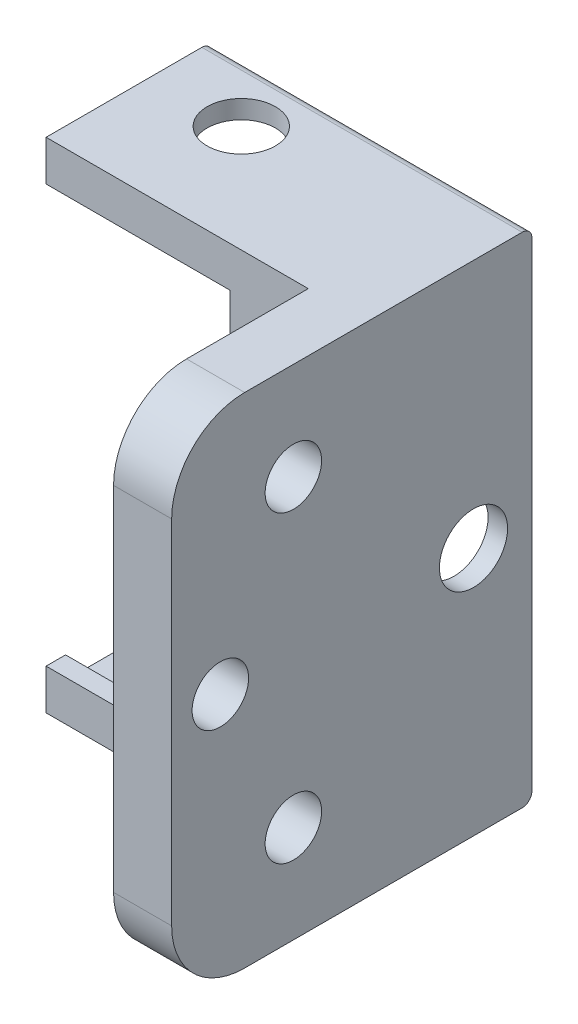
SolidWorks part; units mm, degrees
ref_plane "Front Plane" through (0, 0, 0) normal (0, 0, 1) x (1, 0, 0)
ref_plane "Top Plane" through (0, 0, 0) normal (0, 1, 0) x (1, 0, 0)
ref_plane "Right Plane" through (0, 0, 0) normal (1, 0, 0) x (0, 0, -1)
sketch "Sketch2" plane through (0, 0, 0) normal (0, 0, 1) x (1, 0, 0)
  line L1 (21.85, -23.6) -> (-21.85, -23.6)
  line L2 (21.85, -23.6) -> (21.85, 23.6)
  line L3 (21.85, 23.6) -> (-21.85, 23.6)
  line L4 (-21.85, -23.6) -> (-21.85, 23.6)
  line L5 (21.85, -23.6) -> (-21.85, 23.6) construction
  line L6 (21.85, 23.6) -> (-21.85, -23.6) construction
  line L7 (19.85, -21.4398) -> (-19.85, -21.4398)
  line L8 (19.85, -21.4398) -> (19.85, 21.4398)
  line L9 (19.85, 21.4398) -> (-19.85, 21.4398)
  line L10 (-19.85, -21.4398) -> (-19.85, 21.4398)
  line L11 (19.85, -21.4398) -> (-19.85, 21.4398) construction
  line L12 (19.85, 21.4398) -> (-19.85, -21.4398) construction
  line L13 (19.85, 21.4398) -> (9.85, 21.4398)
  line L14 (19.85, 21.4398) -> (19.85, -21.4398)
  line L15 (19.85, -21.4398) -> (9.85, -21.4398)
  line L16 (9.85, 21.4398) -> (9.85, -21.4398)
  point P0 (0, 0)
  point P6 (0, 0)
  dimension "D1" = 43.7
  dimension "D2" = 47.2
  dimension "D3" = 2
  dimension "D4" = 10
extrude "Boss-Extrude1" add sketch "Sketch2" along normal blind 2 contours L9 L16 L7 L8 | L4 L1 L2 L3 L7 L10 L9 L8
sketch "Sketch3" plane through (0, 0, 2) normal (0, 0, 1) x (1, 0, 0)
  line L8 (-23.85, 25.6) -> (-23.85, -25.6)
  line L9 (-23.85, -25.6) -> (23.85, -25.6)
  line L10 (23.85, -25.6) -> (23.85, 25.6)
  line L11 (23.85, 25.6) -> (-23.85, 25.6)
  line L12 (-23.85, 25.6) -> (-23.85, -25.6)
  line L13 (-23.85, -25.6) -> (23.85, -25.6)
  line L14 (23.85, -25.6) -> (23.85, 25.6)
  line L15 (23.85, 25.6) -> (-23.85, 25.6)
  line L20 (-21.85, 23.6) -> (-21.85, -23.6)
  line L21 (21.85, 23.6) -> (-21.85, 23.6)
  line L22 (21.85, -23.6) -> (21.85, 23.6)
  line L23 (-21.85, -23.6) -> (21.85, -23.6)
  line L24 (-21.85, 23.6) -> (-21.85, -23.6)
  line L25 (21.85, 23.6) -> (-21.85, 23.6)
  line L26 (21.85, -23.6) -> (21.85, 23.6)
  line L27 (-21.85, -23.6) -> (21.85, -23.6)
  dimension "D1" = 2
  dimension "D2" = 0
extrude "Boss-Extrude2" add sketch "Sketch3" against normal blind 17 contours L12 L13 L14 L15
sketch "Sketch5" plane through (0, -25.6, 0) normal (0, -1, 0) x (1, 0, 0)
  line L0 (-23.85, -15) -> (23.85, -15) construction
  point P0 (0, -9)
  dimension "D1" = 6
sketch "Sketch16" plane through (23.85, 0, 0) normal (1, 0, 0) x (0, 0, -1)
  line L0 (15, -25.6) -> (15, 25.6) construction
  point P0 (9, 0)
  dimension "D1" = 6
hole_wizard "M6 Clearance Hole1" positions "Sketch6" profile "Sketch7" hole size "M6" standard "ANSI Metric" end condition through all
sketch "Sketch6" plane through (0, -25.6, 0) normal (0, -1, 0) x (-1, 0, 0)
  point P0 (0, 9)
sketch "Sketch7" plane through (0, -25.6, -9) normal (1, 0, 0) x (0, 0, -1)
  line L0 (0, 0) -> (0, 51.2)
  line L1 (0, 51.2) -> (3.5, 51.2)
  line L2 (3.5, 51.2) -> (3.5, 0)
  line L5 (3.5, 0) -> (0, 0)
  line L11 (0, -6.35) -> (0, 107.95) construction
  dimension "Thru Hole Dia." = 7
  dimension "Thru Hole Depth" = 51.2
hole_wizard "M6 Clearance Hole2" positions "Sketch17" profile "Sketch18" hole size "M6" standard "ANSI Metric" end condition through all
sketch "Sketch17" plane through (23.85, 0, 0) normal (1, 0, 0) x (0, 0, -1)
  point P0 (9, 0)
sketch "Sketch18" plane through (23.85, 0, -9) normal (0, 1, 0) x (0, 0, -1)
  line L0 (0, 0) -> (0, 47.7)
  line L1 (0, 47.7) -> (3.5, 47.7)
  line L2 (3.5, 47.7) -> (3.5, 0)
  line L5 (3.5, 0) -> (0, 0)
  line L11 (0, -6.35) -> (0, 107.95) construction
  dimension "Thru Hole Dia." = 7
  dimension "Thru Hole Depth" = 47.7
sketch "Sketch9" plane through (0, 0, 2) normal (0, 0, 1) x (1, 0, 0)
  line L0 (23.85, 25.6) -> (-23.85, 25.6) construction
  line L1 (23.85, -25.6) -> (17.881, -25.6)
  line L2 (23.85, -25.6) -> (23.85, 25.6)
  line L3 (23.85, 25.6) -> (17.881, 25.6)
  line L4 (17.881, -25.6) -> (17.881, 25.6)
extrude "Boss-Extrude3" add sketch "Sketch9" along normal blind 20
sketch "Sketch10" plane through (23.85, 0, 0) normal (1, 0, 0) x (0, 0, -1)
  line L0 (-9.5, 15.6) -> (-9.5, -15.6)
  line L1 (-22, -25.6) -> (-22, 25.6) construction
  line L2 (15, -25.6) -> (-22, -25.6) construction
  line L3 (15, 25.6) -> (-22, 25.6) construction
  point P3 (-9.5, 0)
  point P9 (-17, 0)
  dimension "D1" = 12.5
  dimension "D2" = 10
  dimension "D3" = 10
  dimension "D4" = 5
hole_wizard "M5 Clearance Hole1" positions "Sketch11" profile "Sketch12" hole size "M5" standard "ANSI Metric" end condition through all
sketch "Sketch11" plane through (23.85, 0, 0) normal (1, 0, 0) x (0, 0, -1)
  point P0 (-9.5, -15.6)
  point P3 (-9.5, 15.6)
  point P6 (-17, 0)
sketch "Sketch12" plane through (23.85, -15.6, 9.5) normal (0, 1, 0) x (0, 0, -1)
  line L0 (0, 0) -> (0, 47.7)
  line L1 (0, 47.7) -> (2.9, 47.7)
  line L2 (2.9, 47.7) -> (2.9, 0)
  line L5 (2.9, 0) -> (0, 0)
  line L11 (0, -6.35) -> (0, 107.95) construction
  dimension "Thru Hole Dia." = 5.8
  dimension "Thru Hole Depth" = 47.7
fillet "Fillet1" radius 7.5 2 edges at (20.8655, 25.6, 22) (20.8655, -25.6, 22)
fillet "Fillet2" radius 1 2 edges at (0, 25.6, -15) (0, -25.6, -15)
sketch "Sketch15" plane through (0, 0, 2) normal (0, 0, 1) x (1, 0, 0)
  line L0 (-23.85, -25.6) -> (17.881, -25.6) construction
  line L1 (-23.85, 25.6) -> (-9.0471, 25.6)
  line L2 (-23.85, 25.6) -> (-23.85, -25.6)
  line L3 (-23.85, -25.6) -> (-9.0471, -25.6)
  line L4 (-9.0471, 25.6) -> (-9.0471, -25.6)
extrude "Cut-Extrude1" cut sketch "Sketch15" against normal through all
sketch "Sketch19" plane through (0, 0, -15) normal (0, 0, -1) x (-1, 0, 0)
  line L0 (-21.85, -23.6) -> (-21.85, 23.6) construction
  line L1 (13.5486, -23.7) -> (-21.85, -23.7)
  line L2 (13.5486, -23.7) -> (13.5486, 23.7)
  line L3 (13.5486, 23.7) -> (-21.85, 23.7)
  line L4 (-21.85, -23.7) -> (-21.85, 23.7)
  line L5 (13.5486, -23.7) -> (-21.85, 23.7) construction
  line L6 (13.5486, 23.7) -> (-21.85, -23.7) construction
  line L7 (-21.85, 23.6) -> (9.0471, 23.6) construction
  point P0 (-4.1507, 0)
  dimension "D1" = 0.1
  dimension "D2" = 0
extrude "Cut-Extrude2" cut sketch "Sketch19" against normal up to surface (15 mm away) up to face at (3.4014, 0, 0)
